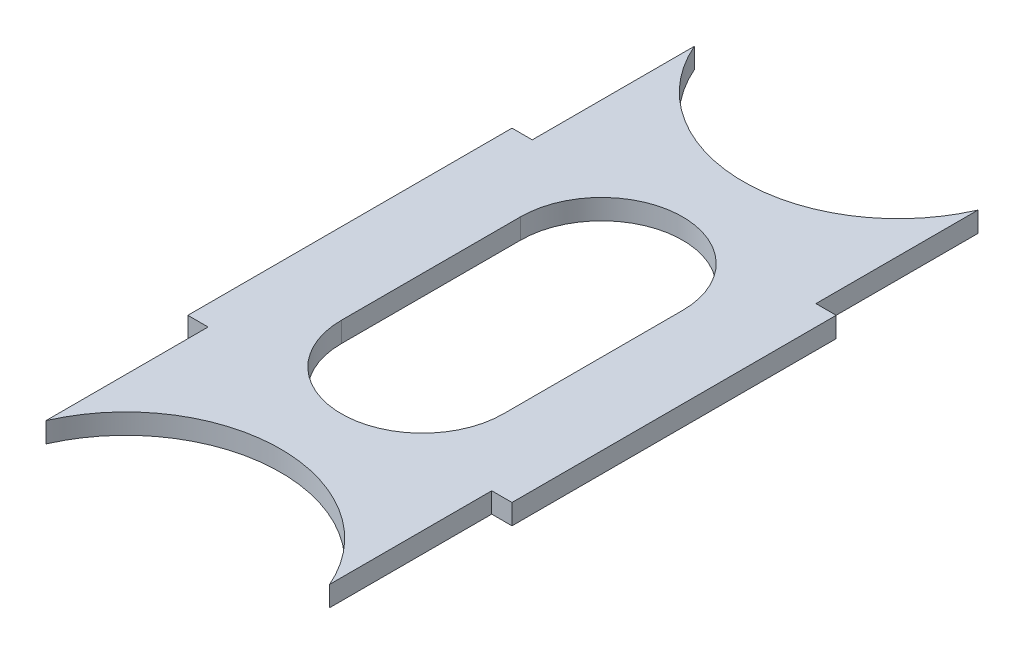
SolidWorks part; units mm, degrees
material "AISI 4130 Steel, annealed at 865C"
ref_plane "X-Y Datum" through (0, 0, 0) normal (0, 0, 1) x (1, 0, 0)
ref_plane "X-Z Datum" through (0, 0, 0) normal (0, 1, 0) x (1, 0, 0)
ref_plane "Y-Z Datum" through (0, 0, 0) normal (1, 0, 0) x (0, 0, -1)
sketch "Sketch1" plane through (0, 0, 0) normal (0, 1, 0) x (1, 0, 0)
  line L0 (11.1125, -12.7) -> (12.7, -12.7)
  line L1 (11.1125, 25.4) -> (-11.1125, 25.4) construction
  line L2 (11.1125, 25.4) -> (11.1125, -25.4)
  line L3 (11.1125, -25.4) -> (-11.1125, -25.4) construction
  line L4 (-11.1125, 25.4) -> (-11.1125, -25.4)
  line L5 (11.1125, 25.4) -> (-11.1125, -25.4) construction
  line L6 (11.1125, -25.4) -> (-11.1125, 25.4) construction
  line L7 (12.7, -12.7) -> (12.7, 12.7)
  line L8 (12.7, 12.7) -> (11.1125, 12.7)
  line L9 (0, -55) -> (0, 55) construction
  line L10 (-12.7, -12.7) -> (-12.7, 12.7)
  line L11 (-12.7, 12.7) -> (-11.1125, 12.7)
  line L12 (-11.1125, -12.7) -> (-12.7, -12.7)
  line L13 (0, 7.0198) -> (0, -7.0198) construction
  line L18 (6.35, 7.0198) -> (6.35, -7.0198)
  line L19 (-6.35, 7.0198) -> (-6.35, -7.0198)
  line L20 (0, -18.1323) -> (0, -13.3698) construction
  line L21 (6.35, 0) -> (11.1125, 0) construction
  arc A1 (11.1125, -25.4) -> (-11.1125, -25.4) centre (0, -30.2617) ccw
  arc A2 (-11.1125, 25.4) -> (11.1125, 25.4) centre (0, 30.2617) ccw
  arc A3 (6.35, 7.0198) -> (-6.35, 7.0198) centre (0, 7.0198) ccw
  arc A4 (-6.35, -7.0198) -> (6.35, -7.0198) centre (0, -7.0198) ccw
  point P0 (0, 0)
  point P12 (12.7, 0)
  point P19 (0, 0)
  point P22 (0, 0)
  dimension "D1" = 1.5875
  dimension "D2" = 25.4
  dimension "D3" = 22.225
  dimension "D4" = 50.8
  dimension "D5" = 4.7625
extrude "Boss-Extrude1" add sketch "Sketch1" along normal blind 1.5875
